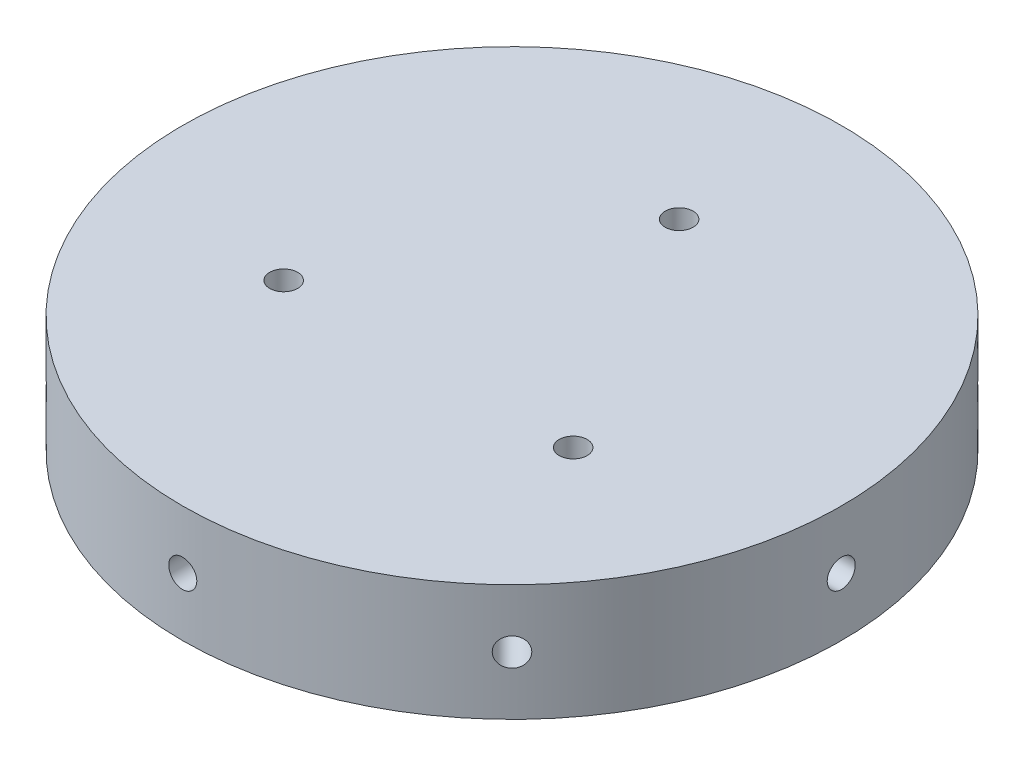
SolidWorks part; units mm, degrees
ref_plane "정면" through (0, 0, 0) normal (0, 0, 1) x (1, 0, 0)
ref_plane "윗면" through (0, 0, 0) normal (0, 1, 0) x (1, 0, 0)
ref_plane "우측면" through (0, 0, 0) normal (1, 0, 0) x (0, 0, -1)
sketch "스케치1" plane through (0, 0, 0) normal (0, 1, 0) x (1, 0, 0)
  circle A0 centre (0, 0) radius 28.5
  circle A1 centre (0, 0) radius 22.065 construction
  dimension "D1" = 57
  dimension "D2" = 44.13
extrude "보스-돌출1" add sketch "스케치1" along normal blind 10
sketch "스케치36" plane through (0, 0, 0) normal (0, -1, 0) x (1, 0, 0)
  line L0 (0, 23.13) -> (0, 14.33)
  circle A0 centre (0, 0) radius 23.13 construction
  circle A1 centre (0, 14.33) radius 3.85
  circle A2 centre (12.4101, -7.165) radius 3.85
  circle A3 centre (-12.4101, -7.165) radius 3.85
  point P12 (0, 0)
  dimension "D1" = 46.26
  dimension "D3" = 7.7
  dimension "D2" = 8.8
  dimension "D4" = 3
extrude "보스-돌출5" add sketch "스케치36" along normal blind 5
ref_plane "평면1" through (-28.5, 0, 0) normal (-1, 0, 0) x (0, 0, 1)
sketch "스케치37" plane through (-28.5, 0, 0) normal (-1, 0, 0) x (0, 0, 1)
  point P0 (0, 5)
  dimension "D1" = 5
hole_wizard "M2 여유 구멍1" positions "스케치40" profile "스케치41" hole size "M2" standard "ISO"
sketch "스케치40" plane through (-28.5, 0, 0) normal (-1, 0, 0) x (0, 0, 1)
  point P0 (0, 5)
sketch "스케치41" plane through (-28.5, 5, 0) normal (0, 1, 0) x (0, 0, 1)
  line L0 (0, 0) -> (0, 15.721)
  line L1 (0, 15.721) -> (1.2, 15)
  line L2 (1.2, 15) -> (1.2, 0)
  line L5 (1.2, 0) -> (0, 0)
  line L10 (0, 15.721) -> (-1.2, 15) construction
  line L11 (0, -6.35) -> (0, 107.95) construction
  dimension "구멍 지름" = 2.4
  dimension "구멍 깊이" = 15
  dimension "드릴 각도" = 118
pattern_circular "원형 패턴4" count 8 over 360 about axis through (0, 10, 0) along (0, 1, 0) of "M2 여유 구멍1"
sketch "스케치42" plane through (0, 10, 0) normal (0, 1, 0) x (1, 0, 0)
  circle A0 centre (0, 0) radius 39.2152
  circle A1 centre (0, 0) radius 28.25
  dimension "D1" = 56.5
extrude "컷-돌출1" cut sketch "스케치42" against normal through all
sketch "스케치43" plane through (0, 0, 0) normal (0, -1, 0) x (1, 0, 0)
  point P0 (0, 14.33)
  point P1 (-12.4101, -7.165)
  point P3 (12.4101, -7.165)
  point P9 (12.4101, 7.165)
  point P10 (-12.4101, 7.165)
  point P11 (0, -14.33)
  point P12 (0, 0)
  dimension "D1" = 2
hole_wizard "M2 여유 구멍3" positions "스케치46" profile "스케치47" hole size "M2" standard "ISO" end condition through all
sketch "스케치46" plane through (0, 0, 0) normal (0, -1, 0) x (-1, 0, 0)
  point P0 (-12.4101, -7.165)
  point P3 (0, 14.33)
  point P6 (12.4101, -7.165)
sketch "스케치47" plane through (12.4101, 0, 7.165) normal (1, 0, 0) x (0, 0, -1)
  line L0 (0, 0) -> (0, 10)
  line L1 (0, 10) -> (1.2, 10)
  line L2 (1.2, 10) -> (1.2, 0)
  line L5 (1.2, 0) -> (0, 0)
  line L11 (0, -6.35) -> (0, 107.95) construction
  dimension "관통 구멍 지름" = 2.4
  dimension "관통 구멍 깊이" = 10
